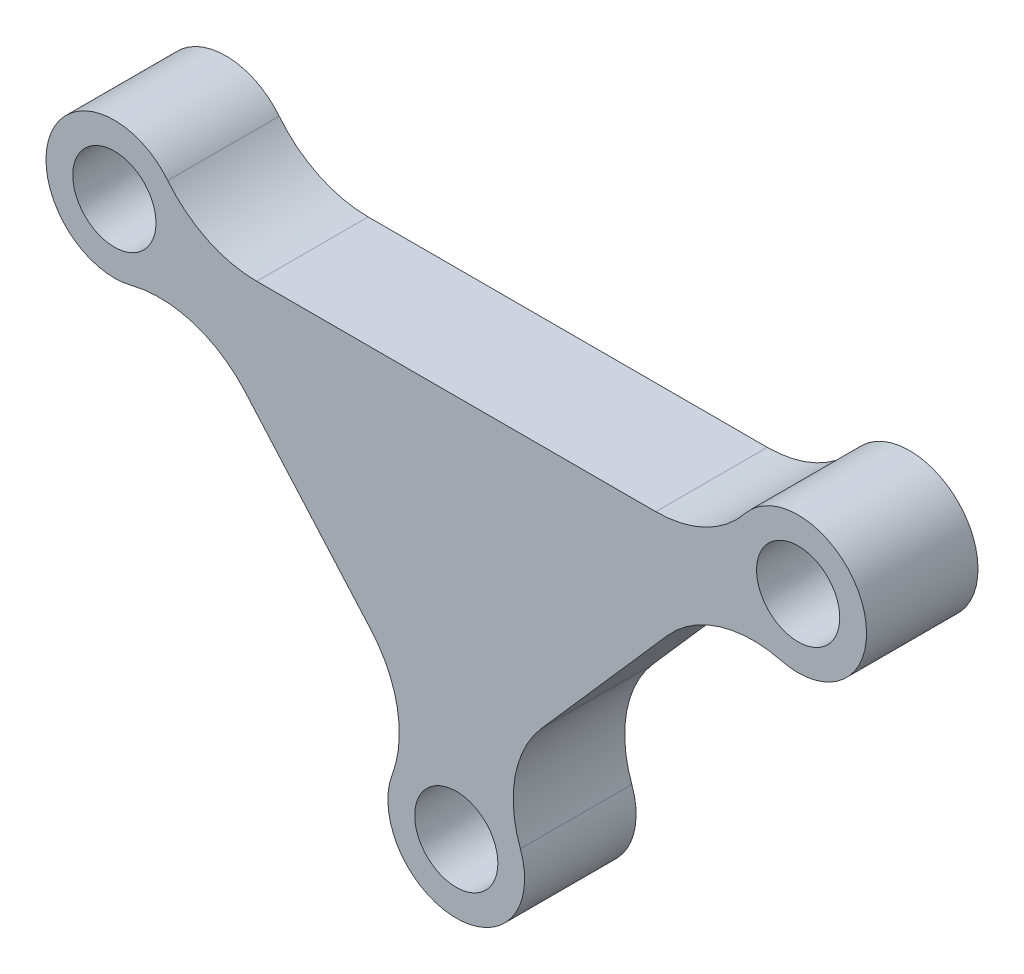
SolidWorks part; units mm, degrees
ref_plane "Plan de face" through (0, 0, 0) normal (0, 0, 1) x (1, 0, 0)
ref_plane "Plan de dessus" through (0, 0, 0) normal (0, 1, 0) x (1, 0, 0)
ref_plane "Plan de droite" through (0, 0, 0) normal (1, 0, 0) x (0, 0, -1)
sketch "Esquisse2" plane through (0, 0, 0) normal (0, 0, 1) x (1, 0, 0)
  line L0 (-13.175, 10) -> (13.175, 10)
  line L1 (13.175, 10) -> (0, -5)
  line L2 (0, -5) -> (-13.175, 10)
  line L3 (0, 0) -> (-13.175, 10) construction
  line L4 (0, 0) -> (13.175, 10) construction
  circle A0 centre (-15, 10) radius 3
  circle A1 centre (-15, 10) radius 1.825
  circle A2 centre (15, 10) radius 3
  circle A3 centre (15, 10) radius 1.825
  circle A4 centre (0, -6.825) radius 3
  circle A5 centre (0, -6.825) radius 1.825
  dimension "D2" = 3.65
  dimension "D3" = 6
  dimension "D1" = 5
  dimension "D4" = 10
  dimension "D5" = 15
extrude "Boss.-Extru.1" add sketch "Esquisse2" along normal blind 4.89 contours A4 L1 A2 L0 A0 L2 | L1 A5 L2 A4 | L1 A4 L2 | A3 | A1
fillet "Congé1" radius 5 6 edges at (-12, 10, 2.445) (-12.2089, 8.9001, 2.445) (-0.9084, -3.9658, 2.445) (12.2089, 8.9001, 2.445) (12, 10, 2.445) (0.9084, -3.9658, 2.445)
